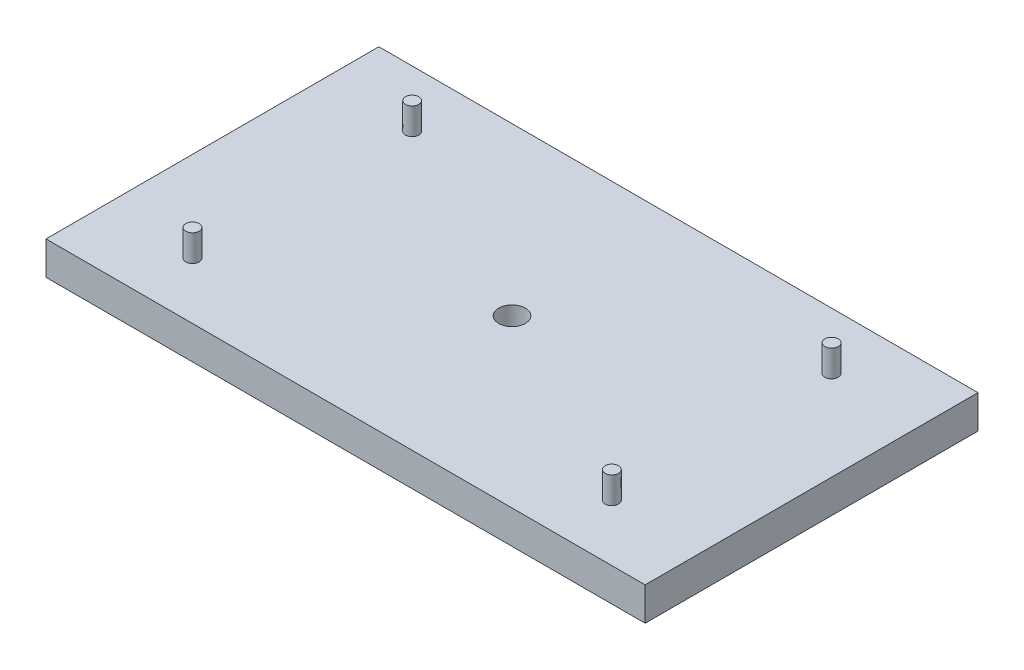
SolidWorks part; units mm, degrees
ref_plane "Front Plane" through (0, 0, 0) normal (0, 0, 1) x (1, 0, 0)
ref_plane "Top Plane" through (0, 0, 0) normal (0, 1, 0) x (1, 0, 0)
ref_plane "Right Plane" through (0, 0, 0) normal (1, 0, 0) x (0, 0, -1)
sketch "Sketch2" plane through (0, 0, 0) normal (0, 1, 0) x (1, 0, 0)
  line L1 (-158.563, 63.9567) -> (-68.563, 63.9567)
  line L2 (-158.563, 63.9567) -> (-158.563, 13.9567)
  line L3 (-158.563, 13.9567) -> (-68.563, 13.9567)
  line L4 (-68.563, 63.9567) -> (-68.563, 13.9567)
  line L5 (-158.563, 63.9567) -> (-68.563, 13.9567) construction
  line L6 (-158.563, 13.9567) -> (-68.563, 63.9567) construction
  point P0 (-113.563, 38.9567)
  dimension "D1" = 90
  dimension "D2" = 50
extrude "Boss-Extrude2" add sketch "Sketch2" along normal blind 5
sketch "Sketch4" plane through (0, 5, 0) normal (0, 1, 0) x (1, 0, 0)
  circle A0 centre (-145.063, 22.4567) radius 1
  circle A1 centre (-145.063, 55.4567) radius 1
  circle A2 centre (-82.063, 55.4567) radius 1
  circle A3 centre (-82.063, 22.4567) radius 1
extrude "Boss-Extrude3" add sketch "Sketch4" along normal blind 4
sketch "Sketch5" plane through (0, 0, 0) normal (0, -1, 0) x (1, 0, 0)
  circle A0 centre (-113.563, -38.9567) radius 2
extrude "Cut-Extrude1" cut sketch "Sketch5" against normal blind 18
